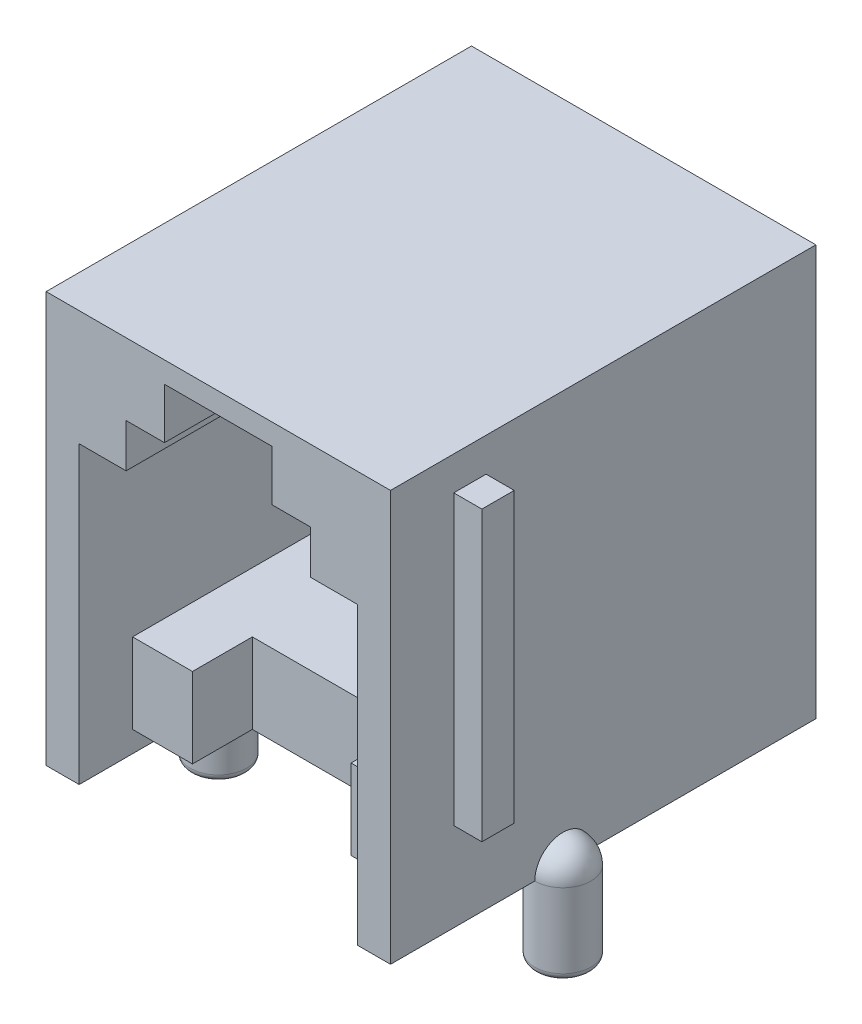
SolidWorks part; units mm, degrees
ref_plane "Front Plane" through (0, 0, 0) normal (0, 0, 1) x (1, 0, 0)
ref_plane "Top Plane" through (0, 0, 0) normal (0, 1, 0) x (1, 0, 0)
ref_plane "Right Plane" through (0, 0, 0) normal (1, 0, 0) x (0, 0, -1)
sketch "Sketch1" plane through (0, 0, 0) normal (0, 0, 1) x (1, 0, 0)
  line L1 (-6.125, -7.3) -> (6.125, -7.3)
  line L2 (-6.125, -7.3) -> (-6.125, 7.3)
  line L3 (-6.125, 7.3) -> (6.125, 7.3)
  line L4 (6.125, -7.3) -> (6.125, 7.3)
  line L5 (-6.125, -7.3) -> (6.125, 7.3) construction
  line L6 (-6.125, 7.3) -> (6.125, -7.3) construction
  point P0 (0, 0)
  dimension "D1" = 12.25
  dimension "D2" = 14.6
extrude "Boss-Extrude1" add sketch "Sketch1" along normal blind 13.13
sketch "Sketch2" plane through (0, 0, 13.13) normal (0, 0, 1) x (1, 0, 0)
  line L0 (0, 7.3) -> (0, 6.55) construction
  line L1 (6.125, 7.3) -> (-6.125, 7.3) construction
  line L2 (0, 0) -> (-6.125, 0) construction
  line L3 (-6.125, 7.3) -> (-6.125, -7.3) construction
  line L4 (0, 0) -> (0, -7.3) construction
  line L5 (-6.125, -7.3) -> (6.125, -7.3) construction
  line L6 (0, 0) -> (6.125, 0) construction
  line L7 (6.125, -7.3) -> (6.125, 7.3) construction
  line L8 (3.28, 3.2) -> (3.28, 4.75)
  line L9 (-4.95, -3.7) -> (4.95, -3.7)
  line L10 (-4.95, -3.7) -> (-4.95, 3.2)
  line L11 (-4.95, 3.2) -> (-3.28, 3.2)
  line L12 (4.95, -3.7) -> (4.95, 3.2)
  line L13 (-4.95, -3.7) -> (4.95, 3.2) construction
  line L14 (-4.95, 3.2) -> (4.95, -3.7) construction
  line L17 (3.28, 4.75) -> (1.915, 4.75)
  line L18 (-3.28, 3.2) -> (-3.28, 4.75)
  line L19 (0, 2.45) -> (0, 0) construction
  line L20 (1.915, 4.75) -> (1.915, 6.55)
  line L23 (1.915, 6.55) -> (-1.915, 6.55)
  line L24 (-1.915, 4.75) -> (-1.915, 6.55)
  line L25 (-1.915, 4.75) -> (-3.28, 4.75)
  line L26 (3.28, 3.2) -> (4.95, 3.2)
  point P5 (0, -0.25)
  dimension "D1" = 9.9
  dimension "D2" = 6.9
  dimension "D3" = 4.1
  dimension "D4" = 2.55
  dimension "D5" = 0.75
  dimension "D6" = 1.915
extrude "Cut-Extrude1" cut sketch "Sketch2" against normal blind 12.07
sketch "Sketch4" plane through (0, 0, 0) normal (0, 0, -1) x (-1, 0, 0)
  line L0 (0, 7.3) -> (0, -7.3) construction
  line L1 (-6.125, 7.3) -> (6.125, 7.3) construction
  line L2 (6.125, -7.3) -> (-6.125, -7.3) construction
  line L4 (5.11, 6.3) -> (-5.11, 6.3)
  line L5 (5.11, 6.3) -> (5.11, 4.45)
  line L6 (5.11, 4.45) -> (-5.11, 4.45)
  line L7 (-5.11, 6.3) -> (-5.11, 4.45)
  line L8 (5.11, 6.3) -> (-5.11, 4.45) construction
  line L9 (5.11, 4.45) -> (-5.11, 6.3) construction
  point P6 (0, 5.375)
  dimension "D1" = 1
  dimension "D2" = 1.85
  dimension "D3" = 10.22
extrude "Cut-Extrude3" cut sketch "Sketch4" against normal blind 10.5
sketch "Sketch5" plane through (0, 0, 0) normal (0, 0, -1) x (-1, 0, 0)
  line L0 (0, 7.3) -> (0, -7.3) construction
  line L1 (-6.125, 7.3) -> (6.125, 7.3) construction
  line L2 (6.125, -7.3) -> (-6.125, -7.3) construction
  line L3 (-6.125, 2.75) -> (-2.85, 2.75) construction
  line L4 (-6.125, -7.3) -> (-6.125, 7.3) construction
  line L5 (6.125, 7.3) -> (6.125, -7.3) construction
  line L6 (-5.11, 4.45) -> (5.11, 4.45) construction
  line L7 (-1.814, -3.55) -> (1.814, -3.55) construction
  line L8 (-2.332, 2.75) -> (2.332, 2.75) construction
  line L9 (2.85, 2.75) -> (6.125, 2.75) construction
  line L10 (-1.814, -3.55) -> (-1.296, -3.55)
  line L15 (-1.296, 2.75) -> (-1.296, -3.55)
  line L16 (-1.814, 2.75) -> (-1.814, -3.55)
  line L17 (-1.814, 2.75) -> (-1.296, 2.75)
  line L18 (-0.778, -3.55) -> (-0.26, -3.55)
  line L19 (-0.26, 2.75) -> (-0.26, -3.55)
  line L20 (-0.778, 2.75) -> (-0.778, -3.55)
  line L21 (-0.778, 2.75) -> (-0.26, 2.75)
  line L22 (0.778, 2.75) -> (0.26, 2.75)
  line L23 (0.26, 2.75) -> (0.26, -3.55)
  line L24 (0.778, 2.75) -> (0.778, -3.55)
  line L25 (0.778, -3.55) -> (0.26, -3.55)
  line L26 (1.814, -3.55) -> (1.296, -3.55)
  line L27 (1.296, 2.75) -> (1.296, -3.55)
  line L28 (1.814, 2.75) -> (1.296, 2.75)
  line L29 (1.814, 2.75) -> (1.814, -3.55)
  dimension "D1" = 1.7
  dimension "D2" = 6.3
  dimension "D4" = 0.518
  dimension "D6" = 3.75
  dimension "D7" = 0.518
extrude "Cut-Extrude4" cut sketch "Sketch5" against normal up to next
sketch "Sketch6" plane through (0, 0, 13.13) normal (0, 0, 1) x (1, 0, 0)
  line L0 (-6.125, -7.3) -> (6.125, -7.3) construction
  line L3 (4.95, -7.3) -> (4.95, -3.7)
  line L4 (4.95, -7.3) -> (-4.95, -7.3)
  line L6 (4.95, -3.7) -> (-4.95, -3.7)
  line L7 (-4.95, -7.3) -> (-4.95, -3.7)
extrude "Cut-Extrude5" cut sketch "Sketch6" against normal blind 1.9
sketch "Sketch10" plane through (0, 0, 11.23) normal (0, 0, 1) x (1, 0, 0)
  line L1 (4.95, -3.7) -> (-4.95, -3.7) construction
  line L3 (2.82, -6.55) -> (2.82, -3.7)
  line L4 (2.82, -6.55) -> (-2.82, -6.55)
  line L6 (2.82, -3.7) -> (-2.82, -3.7)
  line L7 (-2.82, -6.55) -> (-2.82, -3.7)
extrude "Cut-Extrude7" cut sketch "Sketch10" against normal blind 2.13
sketch "Sketch11" plane through (0, 0, 11.23) normal (0, 0, 1) x (1, 0, 0)
  line L0 (4.95, -7.3) -> (4.95, 3.2) construction
  line L1 (-4.95, -7.3) -> (4.95, -7.3)
  line L2 (-4.95, -7.3) -> (-4.95, -6.55)
  line L3 (-4.95, -6.55) -> (4.95, -6.55)
  line L4 (4.95, -7.3) -> (4.95, -6.55)
extrude "Cut-Extrude8" cut sketch "Sketch11" against normal through all
sketch "Sketch12" plane through (0, -7.3, 0) normal (0, -1, 0) x (1, 0, 0)
  line L0 (-6.125, 7) -> (6.125, 7) construction
  line L1 (-6.125, 13.13) -> (-6.125, 0) construction
  line L2 (6.125, 13.13) -> (6.125, 0) construction
  line L3 (-6.125, 13.13) -> (-4.95, 13.13) construction
  line L4 (-6.125, 0) -> (-4.95, 0) construction
  line L5 (0, 7) -> (0, 0) construction
  circle A0 centre (-6.125, 7) radius 1
  circle A1 centre (6.125, 7) radius 1
  dimension "D3" = 2
  dimension "D1" = 6.13
  dimension "D2" = 7
extrude "Boss-Extrude2" add sketch "Sketch12" along normal blind 2.9
sketch "Sketch13" plane through (6.125, 0, 0) normal (1, 0, 0) x (0, 0, -1)
  line L0 (-6, -7.3) -> (-8, -7.3) construction
  line L1 (-7, -6.3) -> (-7, -7.3)
  line L2 (-7, -7.3) -> (-8, -7.3)
  arc A0 (-7, -6.3) -> (-8, -7.3) centre (-7, -7.3) ccw
revolve "Revolve1" add sketch "Sketch13" angle 360 about L1
sketch "Sketch14" plane through (-6.125, 0, 0) normal (-1, 0, 0) x (0, 0, 1)
  line L0 (8, -7.3) -> (6, -7.3) construction
  line L1 (7, -6.3) -> (7, -7.3)
  line L2 (7, -7.3) -> (6, -7.3)
  arc A0 (7, -6.3) -> (6, -7.3) centre (7, -7.3) ccw
revolve "Revolve2" add sketch "Sketch14" angle 360 about L1
fillet "Fillet1" radius 0.25 2 edges at (-6.125, -10.2, 6) (6.125, -10.2, 8)
sketch "Sketch15" plane through (0, -6.55, 0) normal (0, -1, 0) x (1, 0, 0)
  line L0 (-6.125, 2) -> (6.125, 2) construction
  line L1 (-6.125, 6) -> (-6.125, 0) construction
  line L2 (6.125, 6) -> (6.125, 0) construction
  line L3 (6.125, 4.5) -> (-6.125, 4.5) construction
  line L4 (4.95, 0) -> (-4.95, 0) construction
  line L5 (0, 4.5) -> (0, 2) construction
  line L6 (-0.5, 4.5) -> (-0.5, 2) construction
  line L7 (-1.5, 4.5) -> (-1.5, 2) construction
  line L8 (-2.5, 4.5) -> (-2.5, 2) construction
  line L9 (-0.75, 4.75) -> (-0.75, 4.25)
  line L10 (-0.75, 4.25) -> (-0.25, 4.25)
  line L12 (-0.75, 4.75) -> (-0.25, 4.75)
  line L13 (-0.25, 4.25) -> (-0.25, 4.75)
  line L14 (-0.75, 4.25) -> (-0.25, 4.75) construction
  line L15 (-0.75, 4.75) -> (-0.25, 4.25) construction
  line L16 (2.5, 4.5) -> (2.5, 2) construction
  line L17 (-1.75, 1.75) -> (-1.25, 1.75)
  line L18 (-1.75, 1.75) -> (-1.75, 2.25)
  line L19 (-1.75, 2.25) -> (-1.25, 2.25)
  line L20 (-1.25, 1.75) -> (-1.25, 2.25)
  line L21 (-1.75, 1.75) -> (-1.25, 2.25) construction
  line L22 (-1.75, 2.25) -> (-1.25, 1.75) construction
  line L29 (1.5, 4.5) -> (1.5, 2) construction
  line L30 (0.5, 4.5) -> (0.5, 2) construction
  line L31 (-6.125, 7) -> (6.125, 7) construction
  line L32 (0.25, 1.75) -> (0.75, 1.75)
  line L33 (0.25, 1.75) -> (0.25, 2.25)
  line L34 (0.25, 2.25) -> (0.75, 2.25)
  line L35 (0.75, 1.75) -> (0.75, 2.25)
  line L36 (0.25, 1.75) -> (0.75, 2.25) construction
  line L37 (0.25, 2.25) -> (0.75, 1.75) construction
  line L38 (1.25, 4.25) -> (1.75, 4.25)
  line L39 (1.25, 4.25) -> (1.25, 4.75)
  line L40 (1.25, 4.75) -> (1.75, 4.75)
  line L41 (1.75, 4.25) -> (1.75, 4.75)
  line L42 (1.25, 4.25) -> (1.75, 4.75) construction
  line L43 (1.25, 4.75) -> (1.75, 4.25) construction
  dimension "D1" = 2
  dimension "D2" = 2.5
  dimension "D3" = 0.5
  dimension "D4" = 1.5
  dimension "D5" = 2.5
  dimension "D6" = 0.5
  dimension "D7" = 0.5
  dimension "D8" = 0.5
  dimension "D9" = 0.5
  dimension "D12" = 0.5
  dimension "D13" = 0.5
  dimension "D14" = 0.5
  dimension "D15" = 0.5
extrude "Boss-Extrude3" add sketch "Sketch15" along normal blind 3.7
chamfer "Chamfer1" distance 0.05 angle 45 16 edges at (0.5, -10.25, 1.75) (0.25, -10.25, 2) (0.5, -10.25, 2.25) (0.75, -10.25, 2) (1.5, -10.25, 4.25) (1.25, -10.25, 4.5) (1.5, -10.25, 4.75) (1.75, -10.25, 4.5) (-1.5, -10.25, 1.75) (-1.75, -10.25, 2) (-1.5, -10.25, 2.25) (-1.25, -10.25, 2) (-0.5, -10.25, 4.25) (-0.75, -10.25, 4.5) (-0.5, -10.25, 4.75) (-0.25, -10.25, 4.5)
sketch "Sketch16" plane through (0, -6.55, 0) normal (0, -1, 0) x (1, 0, 0)
  line L0 (-6.125, 7) -> (6.125, 7) construction
  line L1 (4.95, 0) -> (4.95, 11.23) construction
  line L2 (-4.95, 6.7) -> (4.95, 6.7)
  line L3 (-4.95, 6.7) -> (-4.95, 7.3)
  line L4 (-4.95, 7.3) -> (4.95, 7.3)
  line L5 (4.95, 6.7) -> (4.95, 7.3)
  line L6 (-4.95, 6.7) -> (4.95, 7.3) construction
  line L7 (-4.95, 7.3) -> (4.95, 6.7) construction
  point P4 (0, 7)
  dimension "D1" = 0.6
extrude "Boss-Extrude4" add sketch "Sketch16" along normal up to surface (0.75 mm away) up to face at (-5.5667, -7.3, 6.71)
sketch "Sketch17" plane through (0, 0, 0) normal (0, 0, -1) x (-1, 0, 0)
  line L0 (0, 7.3) -> (0, 6.3) construction
  line L1 (-6.125, 7.3) -> (6.125, 7.3)
  line L2 (-6.125, 7.3) -> (-6.125, -7.3)
  line L3 (-6.125, -7.3) -> (-5.125, -7.3)
  line L4 (6.125, 7.3) -> (6.125, -7.3)
  line L5 (5.125, -7.3) -> (5.125, -4.3)
  line L8 (5.125, -4.3) -> (-5.125, -4.3)
  line L9 (-5.125, -7.3) -> (-5.125, -4.3)
  line L10 (5.125, -7.3) -> (6.125, -7.3)
  line L11 (1.814, -3.55) -> (1.814, 2.75) construction
  line L12 (-1.814, 2.75) -> (-1.296, 2.75)
  line L13 (-1.814, 2.75) -> (-1.814, -3.55)
  line L14 (-1.814, -3.55) -> (-1.296, -3.55)
  line L15 (-1.296, 2.75) -> (-1.296, -3.55)
  line L16 (-0.778, 2.75) -> (-0.26, 2.75)
  line L17 (-0.778, 2.75) -> (-0.778, -3.55)
  line L18 (-0.778, -3.55) -> (-0.26, -3.55)
  line L19 (-0.26, 2.75) -> (-0.26, -3.55)
  line L20 (0.26, 2.75) -> (0.778, 2.75)
  line L21 (0.26, 2.75) -> (0.26, -3.55)
  line L22 (0.26, -3.55) -> (0.778, -3.55)
  line L23 (0.778, 2.75) -> (0.778, -3.55)
  line L24 (1.296, 2.75) -> (1.814, 2.75)
  line L25 (1.296, 2.75) -> (1.296, -3.55)
  line L26 (1.296, -3.55) -> (1.814, -3.55)
  line L27 (1.814, 2.75) -> (1.814, -3.55)
  line L29 (5.125, 6.3) -> (-5.125, 6.3)
  line L31 (5.125, 4.45) -> (-5.125, 4.45)
  line L32 (-5.125, 6.3) -> (-5.125, 4.45)
  line L33 (5.125, 6.3) -> (5.125, 4.45)
  line L34 (0, 4.45) -> (0, -4.3) construction
  dimension "D1" = 1
  dimension "D2" = 3
  dimension "D3" = 1
  dimension "D4" = 1.85
  dimension "D5" = 1
extrude "Boss-Extrude5" add sketch "Sketch17" along normal blind 2
sketch "Sketch18" plane through (6.125, 0, 0) normal (1, 0, 0) x (0, 0, -1)
  line L0 (-13.13, 7.3) -> (2, 7.3) construction
  line L1 (-10.88, 6.1) -> (-9.73, 6.1)
  line L2 (-10.88, 6.1) -> (-10.88, -4.15)
  line L3 (-10.88, -4.15) -> (-9.73, -4.15)
  line L4 (-9.73, 6.1) -> (-9.73, -4.15)
  line L5 (-13.13, -7.3) -> (-13.13, 7.3) construction
  point P4 (-10.305, 6.1)
  dimension "D1" = 1.15
  dimension "D2" = 1.2
  dimension "D3" = 2.25
  dimension "D4" = 10.25
extrude "Boss-Extrude6" add sketch "Sketch18" along normal blind 1
mirror "Mirror1" about plane through (0, 0, 0) normal (1, 0, 0) of "Boss-Extrude6"
